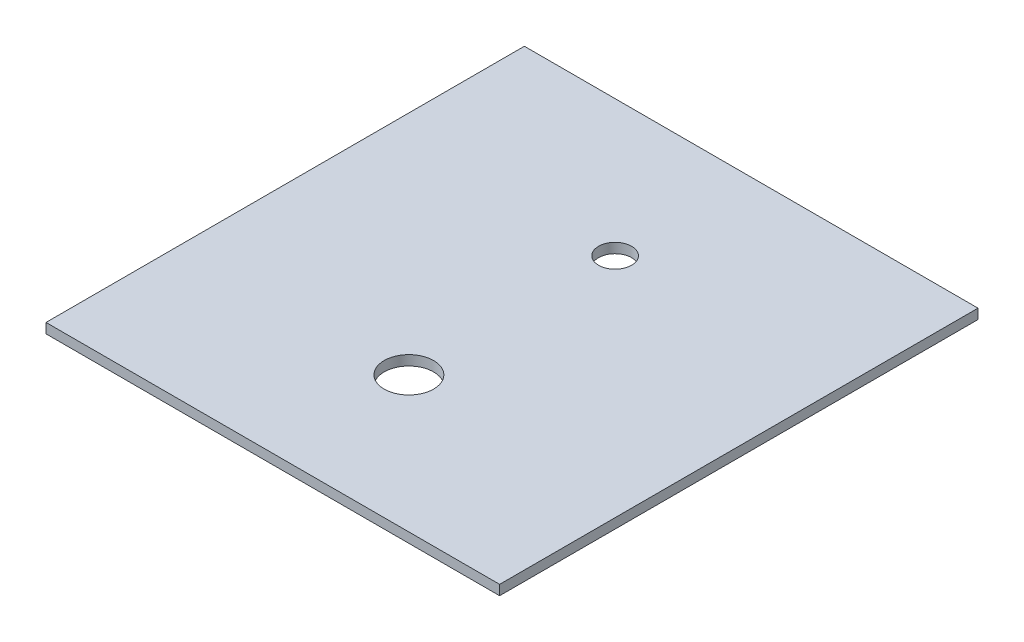
SolidWorks part; units mm, degrees
ref_plane "Front Plane" through (0, 0, 0) normal (0, 0, 1) x (1, 0, 0)
ref_plane "Top Plane" through (0, 0, 0) normal (0, 1, 0) x (1, 0, 0)
ref_plane "Right Plane" through (0, 0, 0) normal (1, 0, 0) x (0, 0, -1)
sketch "Sketch1" plane through (0, 0, 0) normal (0, 1, 0) x (1, 0, 0)
  line L1 (27.5, -29) -> (-27.5, -29)
  line L2 (27.5, -29) -> (27.5, 29)
  line L3 (27.5, 29) -> (-27.5, 29)
  line L4 (-27.5, -29) -> (-27.5, 29)
  line L5 (27.5, -29) -> (-27.5, 29) construction
  line L6 (27.5, 29) -> (-27.5, -29) construction
  circle A0 centre (0, -12.5) radius 3
  circle A1 centre (0, 12.5) radius 2
  point P0 (0, 0)
  dimension "D3" = 6
  dimension "D4" = 12.5
  dimension "D5" = 4
  dimension "D6" = 12.5
  dimension "D1" = 55
  dimension "D2" = 58
extrude "Boss-Extrude1" add sketch "Sketch1" along normal blind 1.2
